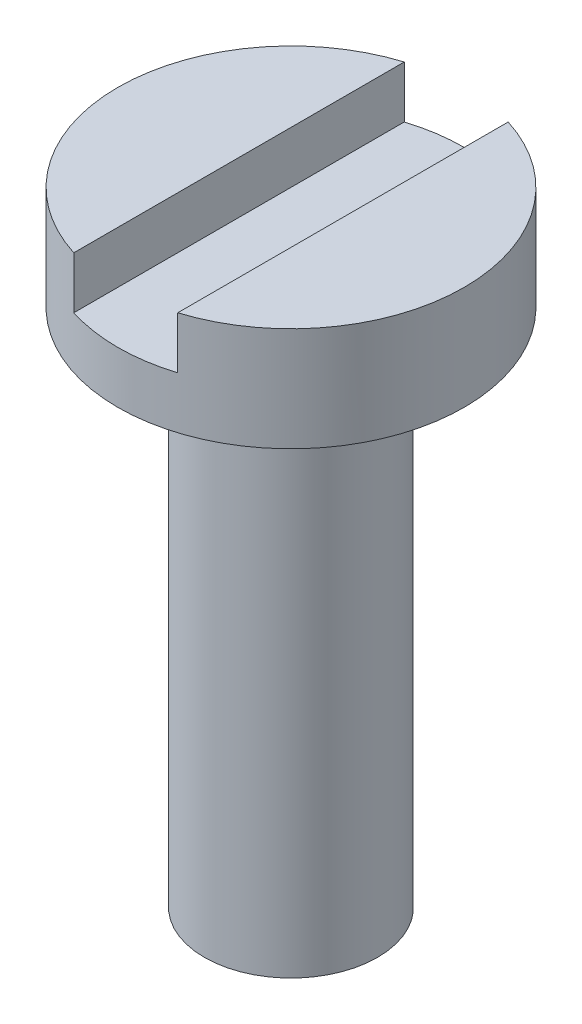
SolidWorks part; units mm, degrees
ref_plane "Front Plane" through (0, 0, 0) normal (0, 0, 1) x (1, 0, 0)
ref_plane "Top Plane" through (0, 0, 0) normal (0, 1, 0) x (1, 0, 0)
ref_plane "Right Plane" through (0, 0, 0) normal (1, 0, 0) x (0, 0, -1)
sketch "Sketch1" plane through (0, 0, 0) normal (0, 1, 0) x (1, 0, 0)
  circle A0 centre (0, 0) radius 2.5
  dimension "D1" = 5
extrude "Boss-Extrude1" add sketch "Sketch1" along normal blind 15
sketch "Sketch2" plane through (0, 15, 0) normal (0, 1, 0) x (1, 0, 0)
  circle A0 centre (0, 0) radius 5
  dimension "D1" = 10
extrude "Boss-Extrude2" add sketch "Sketch2" along normal blind 3
sketch "Sketch3" plane through (0, 18, 0) normal (0, 1, 0) x (1, 0, 0)
  line L0 (0, 5) -> (0, -5) construction
  line L1 (-1.5, 4.7697) -> (-1.5, -4.7697)
  line L2 (1.5, 4.7697) -> (1.5, -4.7697)
  line L3 (-1.5, 5) -> (-1.5, -5) construction
  line L4 (1.5, 5) -> (1.5, -5) construction
  circle A0 centre (0, 0) radius 5 construction
  arc A2 (1.5, 4.7697) -> (-1.5, 4.7697) centre (0, 0) ccw
  circle A3 centre (0, 0) radius 5
  arc A4 (-1.5, -4.7697) -> (1.5, -4.7697) centre (0, 0) ccw
  dimension "D1" = 1.5
  dimension "D2" = 1.5
  dimension "D3" = 0
extrude "Cut-Extrude1" cut sketch "Sketch3" against normal blind 1.5
